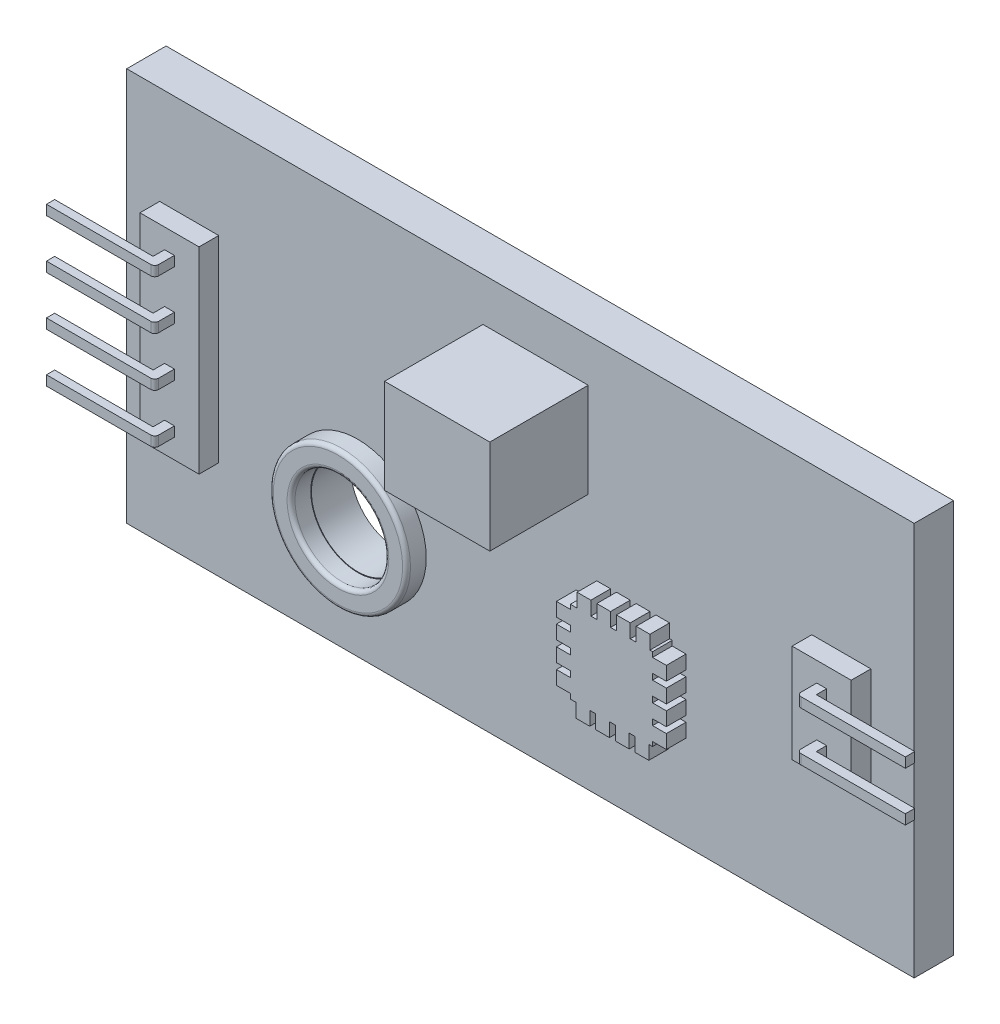
SolidWorks part; units mm, degrees
ref_plane "Front Plane" through (0, 0, 0) normal (0, 0, 1) x (1, 0, 0)
ref_plane "Top Plane" through (0, 0, 0) normal (0, 1, 0) x (1, 0, 0)
ref_plane "Right Plane" through (0, 0, 0) normal (1, 0, 0) x (0, 0, -1)
sketch "Sketch1" plane through (0, 0, 0) normal (0, 0, 1) x (1, 0, 0)
  line L1 (-23.4436, 9.3872) -> (16.5564, 9.3872)
  line L2 (-23.4436, 9.3872) -> (-23.4436, -10.6128)
  line L3 (-23.4436, -10.6128) -> (16.5564, -10.6128)
  line L4 (16.5564, 9.3872) -> (16.5564, -10.6128)
  dimension "D1" = 40
  dimension "D2" = 20
extrude "Boss-Extrude1" add sketch "Sketch1" along normal blind 2
sketch "Sketch2" plane through (0, 0, 2) normal (0, 0, 1) x (1, 0, 0)
  line L1 (-21.7707, 4.3872) -> (-18.7707, 4.3872)
  line L2 (-21.7707, 4.3872) -> (-21.7707, -5.6128)
  line L3 (-21.7707, -5.6128) -> (-18.7707, -5.6128)
  line L4 (-18.7707, 4.3872) -> (-18.7707, -5.6128)
  line L6 (11.3572, -3.1128) -> (14.3572, -3.1128)
  line L7 (11.3572, -3.1128) -> (11.3572, 1.8872)
  line L8 (11.3572, 1.8872) -> (14.3572, 1.8872)
  line L9 (14.3572, -3.1128) -> (14.3572, 1.8872)
  dimension "D1" = 10
  dimension "D2" = 5
  dimension "D3" = 3
  dimension "D4" = 5
  dimension "D5" = 7.5
  dimension "D6" = 3
extrude "Boss-Extrude2" add sketch "Sketch2" along normal blind 1
sketch "Sketch3" plane through (0, 0, 3) normal (0, 0, 1) x (1, 0, 0)
  line L0 (-18.7707, 4.3872) -> (-21.7707, 4.3872) construction
  line L1 (-20.0207, 3.3872) -> (-20.5207, 3.3872)
  line L2 (-20.0207, 3.3872) -> (-20.0207, 2.8872)
  line L3 (-20.0207, 2.8872) -> (-20.5207, 2.8872)
  line L4 (-20.5207, 3.3872) -> (-20.5207, 2.8872)
  line L5 (-20.0207, 0.8872) -> (-20.0207, 0.3872)
  line L6 (-20.0207, 0.8872) -> (-20.5207, 0.8872)
  line L7 (-20.5207, 0.8872) -> (-20.5207, 0.3872)
  line L8 (-20.0207, 0.3872) -> (-20.5207, 0.3872)
  line L9 (-20.0207, -1.6128) -> (-20.0207, -2.1128)
  line L10 (-20.0207, -1.6128) -> (-20.5207, -1.6128)
  line L11 (-20.5207, -1.6128) -> (-20.5207, -2.1128)
  line L12 (-20.0207, -2.1128) -> (-20.5207, -2.1128)
  line L13 (-20.0207, -4.1128) -> (-20.0207, -4.6128)
  line L14 (-20.0207, -4.1128) -> (-20.5207, -4.1128)
  line L15 (-20.5207, -4.1128) -> (-20.5207, -4.6128)
  line L16 (-20.0207, -4.6128) -> (-20.5207, -4.6128)
  line L17 (11.3572, -3.1128) -> (14.3572, -3.1128) construction
  line L18 (12.6072, -2.1128) -> (13.1072, -2.1128)
  line L19 (12.6072, -2.1128) -> (12.6072, -1.6128)
  line L20 (12.6072, -1.6128) -> (13.1072, -1.6128)
  line L21 (13.1072, -2.1128) -> (13.1072, -1.6128)
  line L22 (12.6072, 0.3872) -> (12.6072, 0.8872)
  line L23 (12.6072, 0.3872) -> (13.1072, 0.3872)
  line L24 (13.1072, 0.3872) -> (13.1072, 0.8872)
  line L25 (12.6072, 0.8872) -> (13.1072, 0.8872)
  point P7 (-20.2707, 4.3872)
  point P8 (-20.2707, 3.3872)
  point P26 (12.8572, -3.1128)
  point P27 (12.8572, -2.1128)
  dimension "D1" = 1.5
  dimension "D2" = 3.1729
  dimension "D3" = 0
  dimension "D4" = 0.5
  dimension "D5" = 0.5
  dimension "D7" = 0.5
  dimension "D8" = 0.5
  dimension "D9" = 0
  dimension "D11" = 1
  dimension "D6" = 4
  dimension "D10" = 2
extrude "Boss-Extrude3" add sketch "Sketch3" along normal blind 1
sketch "Sketch5" plane through (-20.5207, 0, 0) normal (-1, 0, 0) x (0, 0, 1)
  line L0 (4, 2.8872) -> (3, 2.8872) construction
  line L1 (4, 3.3872) -> (3.584, 3.3872)
  line L2 (4, 3.3872) -> (4, 2.8872)
  line L3 (4, 2.8872) -> (3.584, 2.8872)
  line L4 (3.584, 3.3872) -> (3.584, 2.8872)
  line L5 (14, 3.3872) -> (14, 2.8872)
  line L6 (14, 3.3872) -> (13.584, 3.3872)
  line L7 (13.584, 3.3872) -> (13.584, 2.8872)
  line L8 (14, 2.8872) -> (13.584, 2.8872)
  line L9 (4, 0.8872) -> (4, 0.3872)
  line L10 (4, 0.8872) -> (3.584, 0.8872)
  line L11 (3.584, 0.8872) -> (3.584, 0.3872)
  line L12 (4, 0.3872) -> (3.584, 0.3872)
  line L13 (4, -1.6128) -> (4, -2.1128)
  line L14 (4, -1.6128) -> (3.584, -1.6128)
  line L15 (3.584, -1.6128) -> (3.584, -2.1128)
  line L16 (4, -2.1128) -> (3.584, -2.1128)
  line L17 (4, -4.1128) -> (4, -4.6128)
  line L18 (4, -4.1128) -> (3.584, -4.1128)
  line L19 (3.584, -4.1128) -> (3.584, -4.6128)
  line L20 (4, -4.6128) -> (3.584, -4.6128)
  dimension "D1" = 2
  dimension "D2" = 4
extrude "Boss-Extrude4" add sketch "Sketch5" along normal blind 5 contours L2 L1 L4 L3 | L9 L12 L11 L10 | L13 L16 L15 L14 | L17 L20 L19 L18
fillet "Fillet1" radius 0.2 4 edges at (-20.0207, 3.1372, 4) (-20.0207, 0.6372, 4) (-20.0207, -1.8628, 4) (-20.0207, -4.3628, 4)
sketch "Sketch7" plane through (13.1072, 0, 0) normal (1, 0, 0) x (0, 0, -1)
  line L0 (-4, -1.6128) -> (-3, -1.6128) construction
  line L1 (-4, -2.1128) -> (-3.5221, -2.1128)
  line L2 (-4, -2.1128) -> (-4, -1.6128)
  line L3 (-4, -1.6128) -> (-3.5221, -1.6128)
  line L4 (-3.5221, -2.1128) -> (-3.5221, -1.6128)
  line L5 (-4, 0.3872) -> (-4, 0.8872)
  line L6 (-4, 0.3872) -> (-3.5221, 0.3872)
  line L7 (-3.5221, 0.3872) -> (-3.5221, 0.8872)
  line L8 (-4, 0.8872) -> (-3.5221, 0.8872)
  dimension "D1" = 2
extrude "Boss-Extrude5" add sketch "Sketch7" along normal blind 5
fillet "Fillet3" radius 0.2 2 edges at (12.6072, 0.6372, 4) (12.6072, -1.8628, 4)
sketch "Sketch8" plane through (0, 0, 2) normal (0, 0, 1) x (1, 0, 0)
  line L1 (0, 2.3871) -> (-5.3462, 2.3871)
  line L2 (0, 2.3871) -> (0, 7.1864)
  line L3 (0, 7.1864) -> (-5.3462, 7.1864)
  line L4 (-5.3462, 2.3871) -> (-5.3462, 7.1864)
extrude "Boss-Extrude6" add sketch "Sketch8" along normal blind 5
sketch "Sketch9" plane through (0, 0, 2) normal (0, 0, 1) x (1, 0, 0)
  line L0 (0.0917, -4.8245) -> (-0.6152, -4.8245)
  line L1 (4.2663, -6.077) -> (4.0776, -6.077)
  line L2 (4.2663, -6.077) -> (4.2663, -5.8547)
  line L3 (3.433, -1.9023) -> (3.133, -1.9023)
  line L4 (0.0917, -6.077) -> (0.0917, -5.8245)
  line L5 (-0.6152, -4.8245) -> (-0.6152, -4.1288)
  line L6 (0.0917, -4.1288) -> (-0.6152, -4.1288)
  line L7 (0.0917, -3.8245) -> (-0.6152, -3.8245)
  line L8 (0.0917, -5.1288) -> (0.0917, -4.8245)
  line L9 (0.0917, -5.8245) -> (-0.6152, -5.8245)
  line L10 (0.0917, -5.1288) -> (-0.6152, -5.1288)
  line L11 (-0.6152, -5.8245) -> (-0.6152, -5.1288)
  line L12 (-0.6152, -3.8245) -> (-0.6152, -3.1288)
  line L13 (0.0917, -3.1288) -> (-0.6152, -3.1288)
  line L14 (0.0917, -2.8245) -> (-0.6152, -2.8245)
  line L15 (-0.6152, -2.8245) -> (-0.6152, -2.1288)
  line L16 (0.0917, -2.1288) -> (-0.6152, -2.1288)
  line L17 (2.133, -1.9023) -> (2.133, -1.2023)
  line L18 (1.433, -1.2023) -> (2.133, -1.2023)
  line L19 (1.433, -1.9023) -> (1.433, -1.2023)
  line L20 (3.133, -1.9023) -> (3.133, -1.2023)
  line L21 (0.433, -1.9023) -> (0.0917, -1.9023)
  line L22 (0.433, -1.9023) -> (0.433, -1.2023)
  line L23 (1.133, -1.9023) -> (1.133, -1.2023)
  line L24 (0.433, -1.2023) -> (1.133, -1.2023)
  line L25 (2.433, -1.2023) -> (3.133, -1.2023)
  line L26 (2.433, -1.9023) -> (2.433, -1.2023)
  line L27 (4.133, -1.9023) -> (4.133, -1.2023)
  line L28 (3.433, -1.2023) -> (4.133, -1.2023)
  line L29 (3.433, -1.9023) -> (3.433, -1.2023)
  line L30 (4.2663, -3.8547) -> (4.9663, -3.8547)
  line L31 (4.9663, -3.1547) -> (4.9663, -3.8547)
  line L32 (4.2663, -3.1547) -> (4.9663, -3.1547)
  line L33 (4.2663, -4.8547) -> (4.9663, -4.8547)
  line L34 (4.2663, -2.1547) -> (4.2663, -1.9023)
  line L35 (4.2663, -2.1547) -> (4.9663, -2.1547)
  line L36 (4.2663, -2.8547) -> (4.9663, -2.8547)
  line L37 (4.9663, -2.1547) -> (4.9663, -2.8547)
  line L38 (4.9663, -4.1547) -> (4.9663, -4.8547)
  line L39 (4.2663, -4.1547) -> (4.9663, -4.1547)
  line L40 (4.2663, -5.8547) -> (4.9663, -5.8547)
  line L41 (4.9663, -5.1547) -> (4.9663, -5.8547)
  line L42 (4.2663, -5.1547) -> (4.9663, -5.1547)
  line L43 (3.0776, -6.077) -> (3.0776, -6.777)
  line L44 (3.0776, -6.777) -> (2.3776, -6.777)
  line L45 (2.3776, -6.077) -> (2.3776, -6.777)
  line L46 (2.0776, -6.077) -> (2.0776, -6.777)
  line L47 (3.3776, -6.077) -> (3.0776, -6.077)
  line L48 (4.0776, -6.077) -> (4.0776, -6.777)
  line L49 (3.3776, -6.077) -> (3.3776, -6.777)
  line L50 (4.0776, -6.777) -> (3.3776, -6.777)
  line L51 (2.0776, -6.777) -> (1.3776, -6.777)
  line L52 (1.3776, -6.077) -> (1.3776, -6.777)
  line L53 (1.0776, -6.077) -> (1.0776, -6.777)
  line L54 (1.0776, -6.777) -> (0.3776, -6.777)
  line L55 (0.3776, -6.077) -> (0.3776, -6.777)
  line L56 (2.433, -1.9023) -> (2.133, -1.9023)
  line L57 (1.433, -1.9023) -> (1.133, -1.9023)
  line L58 (4.2663, -3.1547) -> (4.2663, -2.8547)
  line L59 (4.2663, -4.1547) -> (4.2663, -3.8547)
  line L60 (4.2663, -5.1547) -> (4.2663, -4.8547)
  line L61 (1.3776, -6.077) -> (1.0776, -6.077)
  line L62 (2.3776, -6.077) -> (2.0776, -6.077)
  line L63 (0.3776, -6.077) -> (0.0917, -6.077)
  line L64 (0.0917, -4.1288) -> (0.0917, -3.8245)
  line L65 (0.0917, -3.1288) -> (0.0917, -2.8245)
  line L66 (0.0917, -2.1288) -> (0.0917, -1.9023)
  line L67 (4.2663, -1.9023) -> (4.133, -1.9023)
  point P54 (0, 0)
  point P69 (0, 0)
  dimension "D2" = 4.1747
  dimension "D3" = 4.1747
  dimension "D4" = 0.7
  dimension "D5" = 0.7
  dimension "D7" = 0.7
  dimension "D8" = 0.7
  dimension "D10" = 0.7
  dimension "D11" = 0.7
  dimension "D1" = 4
  dimension "D6" = 4
  dimension "D9" = 4
  dimension "D12" = 4
extrude "Boss-Extrude8" add sketch "Sketch9" along normal blind 1
sketch "Sketch10" plane through (0, 0, 2) normal (0, 0, 1) x (1, 0, 0)
  circle A0 centre (-11.7137, -4.5276) radius 2.3493
extrude "Cut-Extrude1" cut sketch "Sketch10" against normal up to next
sketch "Sketch13" plane through (0, 0, 2) normal (0, 0, 1) x (1, 0, 0)
  circle A1 centre (-11.7137, -4.5276) radius 2.3493 construction
  circle A2 centre (-11.7137, -4.5276) radius 3.4849
  point P0 (-11.7137, -2.1784)
  point P1 (-14.063, -4.5276)
  point P4 (-11.7137, -4.5276)
extrude "Boss-Extrude9" add sketch "Sketch13" along normal blind 1
sketch "Sketch14" plane through (0, 0, 2) normal (0, 0, -1) x (-1, 0, 0)
  circle A0 centre (11.7137, -4.5276) radius 2.3493 construction
  circle A1 centre (11.7137, -4.5276) radius 2.3824
  point P0 (9.3644, -4.5276)
  point P1 (11.7137, -2.1784)
  point P4 (11.7137, -4.5276)
extrude "Cut-Extrude2" cut sketch "Sketch14" against normal up to next
fillet "Fillet5" radius 0.2 2 edges at (-8.2288, -4.5276, 3) (-9.3313, -4.5276, 3)
